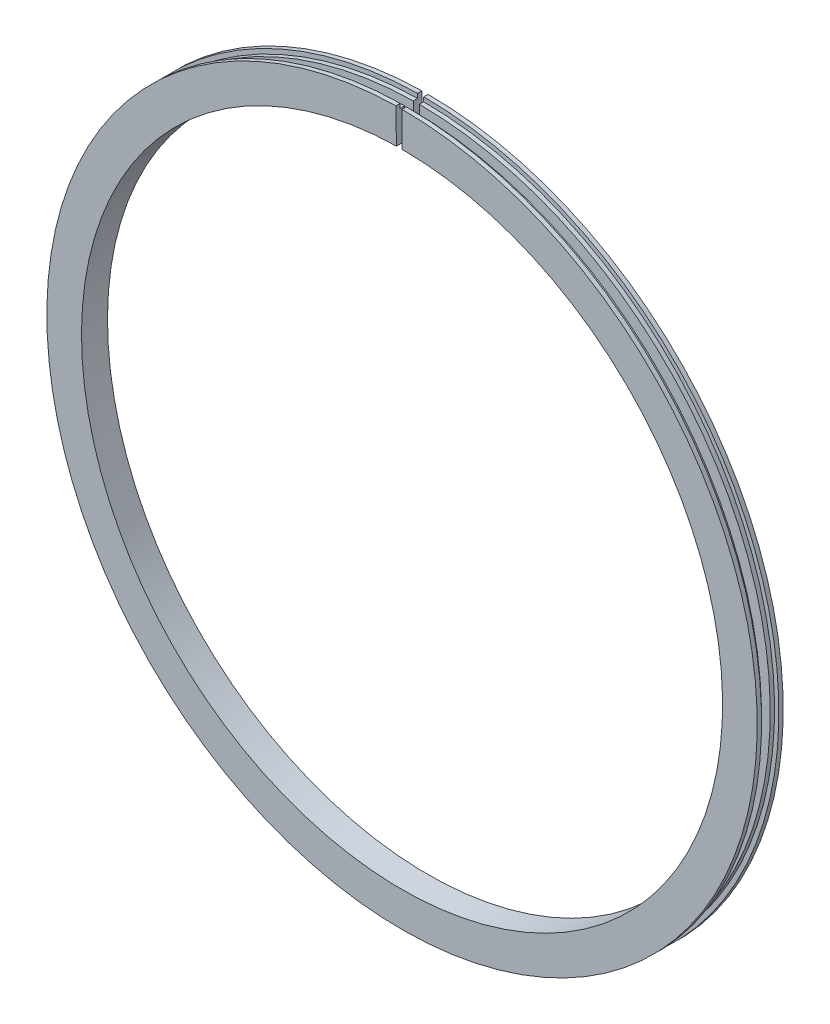
SolidWorks part; units mm, degrees
ref_plane "前视基准面" through (0, 0, 0) normal (0, 0, 1) x (1, 0, 0)
ref_plane "上视基准面" through (0, 0, 0) normal (0, 1, 0) x (1, 0, 0)
ref_plane "右视基准面" through (0, 0, 0) normal (1, 0, 0) x (0, 0, -1)
other "Configuration Table"
sketch "草图2" plane through (0, 0, 0) normal (-1, 0, 0) x (0, 1, 0)
  line L1 (0, 0) -> (0, 14.7628) construction
  line L2 (0, 14.7628) -> (0, -15.4698) construction
  line L3 (37, 0) -> (41, 0)
  line L4 (41, 0) -> (41, 0.5)
  line L5 (41, 0.5) -> (40.5, 0.5)
  line L6 (40.5, 0.5) -> (40.5, 1)
  line L7 (40.5, 1) -> (38.5, 1)
  line L8 (38.5, 1) -> (38.5, 2)
  line L9 (37, 0) -> (37, 3)
  line L10 (37, 1.5) -> (41.7431, 1.5) construction
  line L11 (41, 3) -> (41, 2.5)
  line L12 (41, 2.5) -> (40.5, 2.5)
  line L13 (40.5, 2.5) -> (40.5, 2)
  line L14 (40.5, 2) -> (38.5, 2)
  line L15 (37, 3) -> (41, 3)
  point P18 (38.5, 1.5)
  point P19 (41, 0.25)
  dimension "D1" = 4
  dimension "D2" = 0.5
  dimension "D3" = 2.5
  dimension "D4" = 0.5
  dimension "D5" = 2
  dimension "D6" = 1
  dimension "D7" = 37
revolve "旋转1" add sketch "草图2" angle 359 about L1
